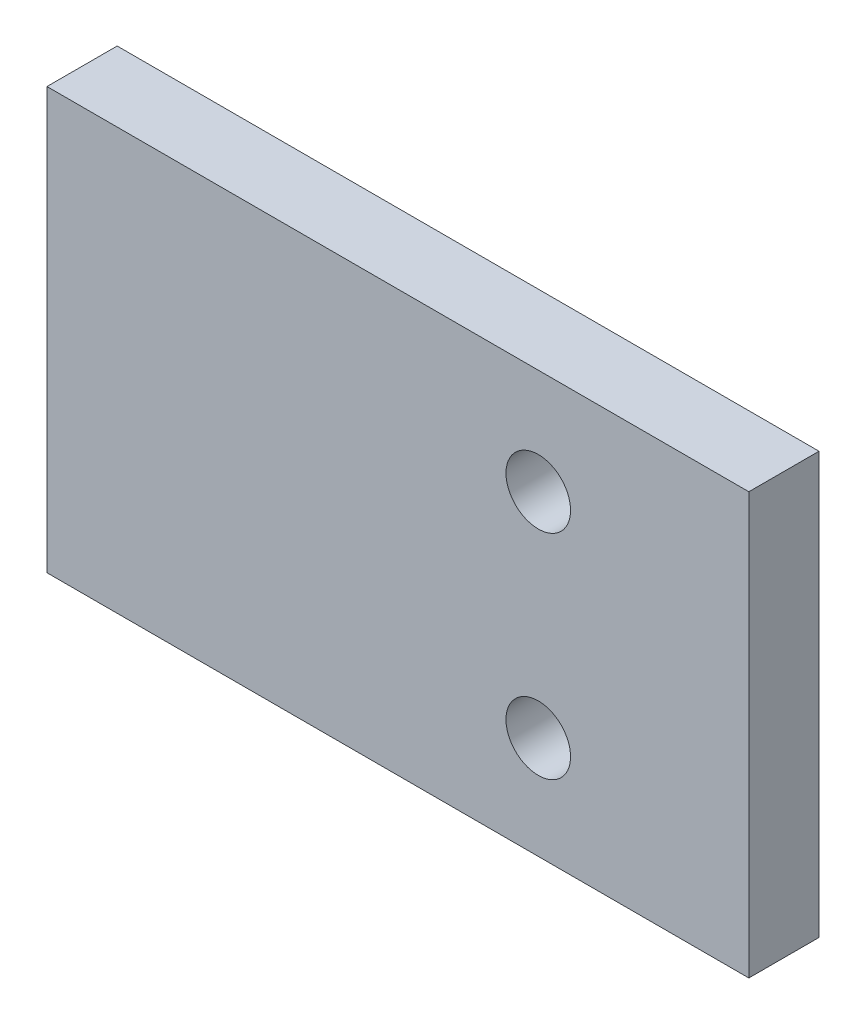
SolidWorks part; units mm, degrees
ref_plane "Front Plane" through (0, 0, 0) normal (0, 0, 1) x (1, 0, 0)
ref_plane "Top Plane" through (0, 0, 0) normal (0, 1, 0) x (1, 0, 0)
ref_plane "Right Plane" through (0, 0, 0) normal (1, 0, 0) x (0, 0, -1)
sketch "Sketch1" plane through (0, 0, 0) normal (0, 0, 1) x (1, 0, 0)
  line L0 (-203.2, 19.05) -> (0, 19.05) construction
  line L1 (-215.9, 0) -> (-184.15, 0)
  line L2 (-215.9, 0) -> (-215.9, 19.05)
  line L3 (-215.9, 19.05) -> (-184.15, 19.05)
  line L4 (-184.15, 0) -> (-184.15, 19.05)
  dimension "D1" = 19.05
  dimension "D2" = 12.7
extrude "Boss-Extrude2" add sketch "Sketch1" along normal blind 3.175 contours L3 L4 L1 L2
sketch "Sketch3" plane through (0, 0, 0) normal (0, 0, -1) x (-1, 0, 0)
  circle A0 centre (193.675, 14.2875) radius 1.4605
  circle A1 centre (193.675, 4.6355) radius 1.4605
  dimension "D1" = 2.921
  dimension "D2" = 2.921
extrude "Cut-Extrude1" cut sketch "Sketch3" against normal blind 9.525
